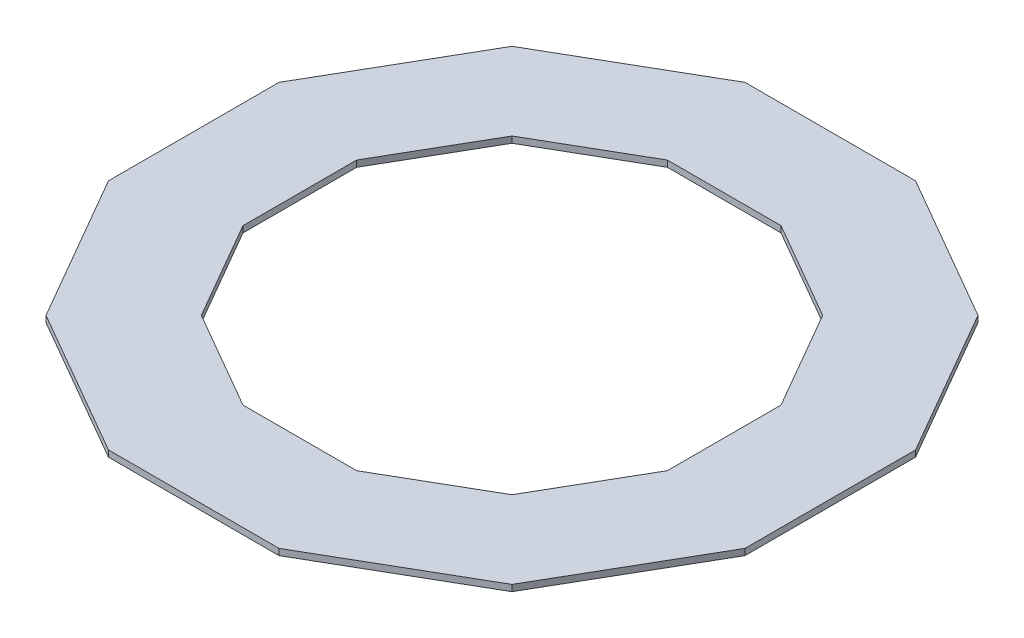
SolidWorks part; units mm, degrees
material "ABS PC"
ref_plane "Front Plane" through (0, 0, 0) normal (0, 0, 1) x (1, 0, 0)
ref_plane "Top Plane" through (0, 0, 0) normal (0, 1, 0) x (1, 0, 0)
ref_plane "Right Plane" through (0, 0, 0) normal (1, 0, 0) x (0, 0, -1)
sketch "Sketch1" plane through (0, 0, 0) normal (0, 1, 0) x (1, 0, 0)
  line L0 (39.444, 147.2071) -> (-39.444, 147.2071)
  line L1 (-39.444, 147.2071) -> (-107.7631, 107.7631)
  line L2 (-107.7631, 107.7631) -> (-147.2071, 39.444)
  line L3 (-147.2071, 39.444) -> (-147.2071, -39.444)
  line L4 (-147.2071, -39.444) -> (-107.7631, -107.7631)
  line L5 (-107.7631, -107.7631) -> (-39.444, -147.2071)
  line L6 (-39.444, -147.2071) -> (39.444, -147.2071)
  line L7 (39.444, -147.2071) -> (107.7631, -107.7631)
  line L8 (107.7631, -107.7631) -> (147.2071, -39.444)
  line L9 (147.2071, -39.444) -> (147.2071, 39.444)
  line L10 (147.2071, 39.444) -> (107.7631, 107.7631)
  line L11 (107.7631, 107.7631) -> (39.444, 147.2071)
  circle A0 centre (0, 0) radius 152.4
  dimension "D1" = 304.8
extrude "Boss-Extrude1" add sketch "Sketch1" against normal blind 2.921 contours L10 L11 L0 L1 L2 L3 L4 L5 L6 L7 L8 L9
sketch "Sketch3" plane through (0, 0, 0) normal (0, 1, 0) x (1, 0, 0)
  line L12 (-71.842, 71.842) -> (-26.296, 98.1381)
  line L13 (-26.296, 98.1381) -> (26.296, 98.1381)
  line L14 (26.296, 98.1381) -> (71.842, 71.842)
  line L15 (71.842, 71.842) -> (98.1381, 26.296)
  line L16 (98.1381, 26.296) -> (98.1381, -26.296)
  line L17 (98.1381, -26.296) -> (71.842, -71.842)
  line L18 (71.842, -71.842) -> (26.296, -98.1381)
  line L19 (26.296, -98.1381) -> (-26.296, -98.1381)
  line L20 (-26.296, -98.1381) -> (-71.842, -71.842)
  line L21 (-71.842, -71.842) -> (-98.1381, -26.296)
  line L22 (-98.1381, -26.296) -> (-98.1381, 26.296)
  line L23 (-98.1381, 26.296) -> (-71.842, 71.842)
  line L24 (-107.7631, 107.7631) -> (-147.2071, 39.444) construction
  line L25 (-39.444, 147.2071) -> (-107.7631, 107.7631) construction
  line L26 (39.444, 147.2071) -> (-39.444, 147.2071) construction
  line L27 (107.7631, 107.7631) -> (39.444, 147.2071) construction
  line L28 (147.2071, 39.444) -> (107.7631, 107.7631) construction
  line L29 (147.2071, -39.444) -> (147.2071, 39.444) construction
  line L30 (107.7631, -107.7631) -> (147.2071, -39.444) construction
  line L31 (39.444, -147.2071) -> (107.7631, -107.7631) construction
  line L32 (-39.444, -147.2071) -> (39.444, -147.2071) construction
  line L33 (-107.7631, -107.7631) -> (-39.444, -147.2071) construction
  line L34 (-147.2071, -39.444) -> (-107.7631, -107.7631) construction
  line L35 (-147.2071, 39.444) -> (-147.2071, -39.444) construction
  line L36 (-39.444, 147.2071) -> (39.444, -147.2071) construction
  line L37 (39.444, 147.2071) -> (-39.444, -147.2071) construction
  circle A0 centre (0, 0) radius 101.6
  dimension "D1" = 203.2
extrude "Cut-Extrude1" cut sketch "Sketch3" against normal through all contours L23 L22 L21 L20 L19 L18 L17 L16 L15 L14 L13 L12
